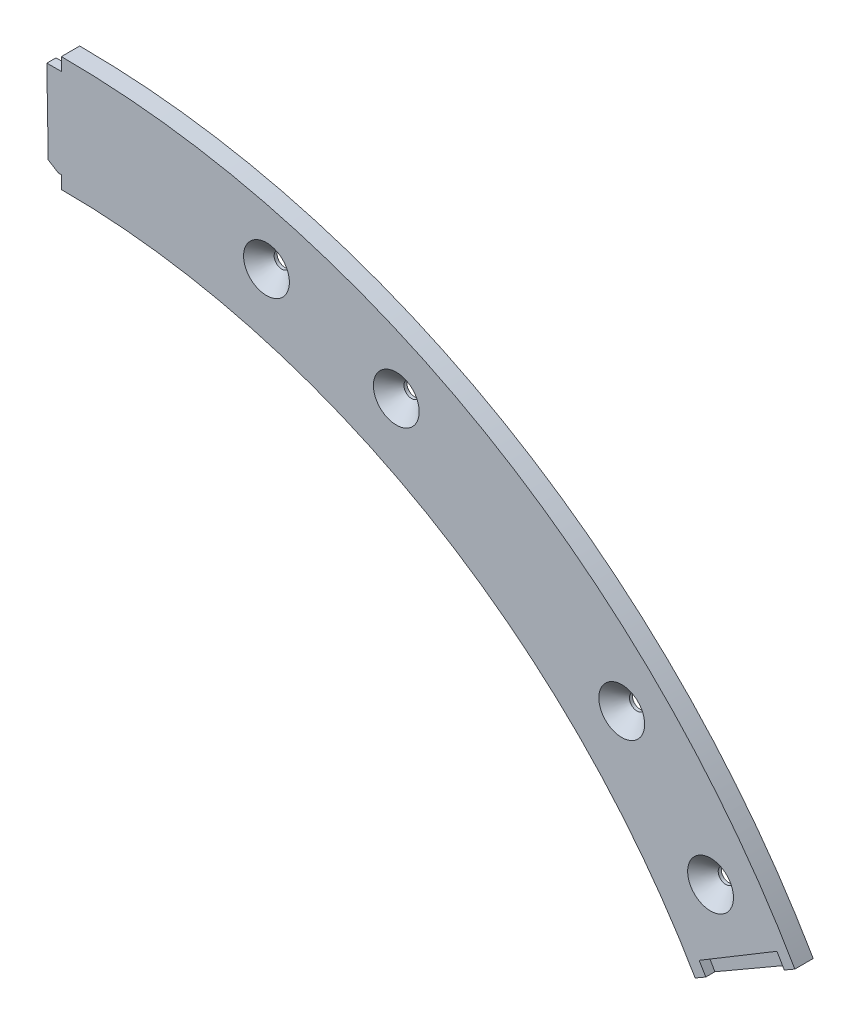
SolidWorks part; units mm, degrees
ref_plane "Plan de face" through (0, 0, 0) normal (0, 0, 1) x (1, 0, 0)
ref_plane "Plan de dessus" through (0, 0, 0) normal (0, 1, 0) x (1, 0, 0)
ref_plane "Plan de droite" through (0, 0, 0) normal (1, 0, 0) x (0, 0, -1)
sketch "Esquisse1" plane through (0, 0, 0) normal (0, 0, 1) x (1, 0, 0)
  line L0 (0, 277.3) -> (0, 239.61)
  line L1 (240.1488, 138.65) -> (207.5083, 119.805)
  arc A0 (0, 239.61) -> (207.5083, 119.805) centre (0, 0) cw
  arc A1 (0, 277.3) -> (240.1488, 138.65) centre (0, 0) cw
  dimension "D1" = 37.69
  dimension "D2" = 277.3
  dimension "D3" = 60
  dimension "D4" = 60
extrude "Boss.-Extru.1" add sketch "Esquisse1" along normal blind 6
sketch "Esquisse2" plane through (0, 0, 6) normal (0, 0, 1) x (1, 0, 0)
  line L0 (0, 277.3) -> (0, 0) construction
  line L1 (67.1558, 250.6288) -> (0, 0) construction
  line L2 (0, 0) -> (109.6568, 235.1597) construction
  line L4 (183.473, 183.473) -> (0, 0) construction
  line L5 (212.5454, 148.8259) -> (0, 0) construction
  line L6 (207.5083, 119.805) -> (0, 0) construction
  circle A0 centre (67.1558, 250.6288) radius 2.5
  circle A1 centre (109.6568, 235.1597) radius 2.5
  circle A3 centre (212.5454, 148.8259) radius 2.5
  circle A4 centre (183.473, 183.473) radius 2.5
  dimension "D2" = 5
  dimension "D4" = 5
  dimension "D11" = 5
  dimension "D8" = 5
  dimension "D1" = 277.3
  dimension "D5" = 10
  dimension "D6" = 259.47
  dimension "D7" = 259.47
  dimension "D12" = 5
  dimension "D13" = 259.47
  dimension "D3" = 15
  dimension "D9" = 259.47
  dimension "D10" = 10
extrude "Enlèv. mat.-Extru.1" cut sketch "Esquisse2" against normal blind 6
chamfer "Chanfrein1" distance 5 angle 45 4 edges at (112.1568, 235.1597, 6) (69.6558, 250.6288, 6) (215.0454, 148.8259, 6) (185.973, 183.473, 6)
sketch "Esquisse6" plane through (0, 0, 0) normal (0.5, -0.866, 0) x (0.866, 0.5, 0)
  line L0 (239.61, 6) -> (277.3, 6) construction
  line L5 (243.61, 6) -> (273.3, 6)
  line L6 (243.61, 6) -> (243.61, 3)
  line L7 (0, 0) -> (0, 25.3099) construction
  line L8 (243.61, 3) -> (273.3, 3)
  line L13 (273.3, 6) -> (273.3, 3)
  line L14 (239.61, 6) -> (239.61, 0) construction
  line L22 (277.3, 6) -> (277.3, 0) construction
  dimension "D1" = 4
  dimension "D2" = 4
  dimension "D3" = 3
revolve "Enlèvement de matière-Révolution1" cut sketch "Esquisse6" angle 1 about L7
sketch "Esquisse7" plane through (0, 0, 0) normal (-1, 0, 0) x (0, 0, 1)
  line L0 (6, 277.3) -> (6, 239.61) construction
  line L1 (6, 273.1) -> (3, 273.1)
  line L2 (6, 273.1) -> (6, 243.81)
  line L3 (6, 243.81) -> (3, 243.81)
  line L4 (3, 273.1) -> (3, 243.81)
  line L5 (6, 277.3) -> (0, 277.3) construction
  line L6 (6, 239.61) -> (0, 239.61) construction
  line L7 (0, 0) -> (-29.4003, 0) construction
  dimension "D1" = 4.2
  dimension "D2" = 4.2
  dimension "D3" = 3
revolve "Révolution2" add sketch "Esquisse7" angle 1 about L7
sketch "Esquisse8" plane through (0, 0, 6) normal (0, 0, 1) x (1, 0, 0)
  line L0 (-4.2915, 245.8571) -> (-0.9806, 243.808)
  line L1 (-4.2551, 243.7729) -> (-4.7663, 273.0584) construction
  line L2 (-0.9806, 243.808) -> (-4.2551, 243.7729)
  line L3 (-4.2551, 243.7729) -> (-4.2915, 245.8571)
  arc A0 (0, 243.81) -> (-4.2551, 243.7729) centre (0, 0) ccw construction
extrude "Enlèv. mat.-Extru.2" cut sketch "Esquisse8" against normal blind 10
equation "\"D7@Esquisse2\"=\"D6@Esquisse2\""
equation "\"D2@Esquisse6\"=\"D1@Esquisse6\""
equation "\"D13@Esquisse2\"=\"D6@Esquisse2\""
equation "\"D9@Esquisse2\"=\"D6@Esquisse2\""
